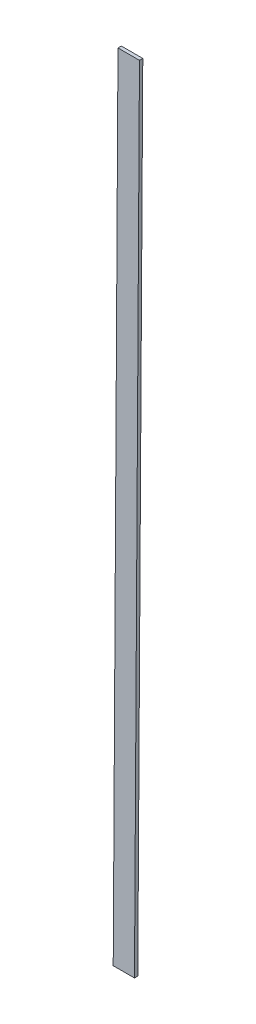
SolidWorks part; units mm, degrees
material "Balsa"
ref_plane "Front Plane" through (0, 0, 0) normal (0, 0, 1) x (1, 0, 0)
ref_plane "Top Plane" through (0, 0, 0) normal (0, 1, 0) x (1, 0, 0)
ref_plane "Right Plane" through (0, 0, 0) normal (1, 0, 0) x (0, 0, -1)
sketch "Sketch1" plane through (0, 0, 0) normal (0, 0, 1) x (1, 0, 0)
  line L0 (-60.3492, -88.4571) -> (-50.1892, -88.4571)
  line L1 (-50.1892, -88.4571) -> (-47.7983, 292.5533)
  line L2 (-47.7983, 292.5533) -> (-58.0702, 292.5533)
  line L3 (-58.0702, 292.5533) -> (-60.3492, -88.4571)
extrude "Boss-Extrude1" add sketch "Sketch1" along normal blind 1.5875 contours L3 L0 L1 L2
